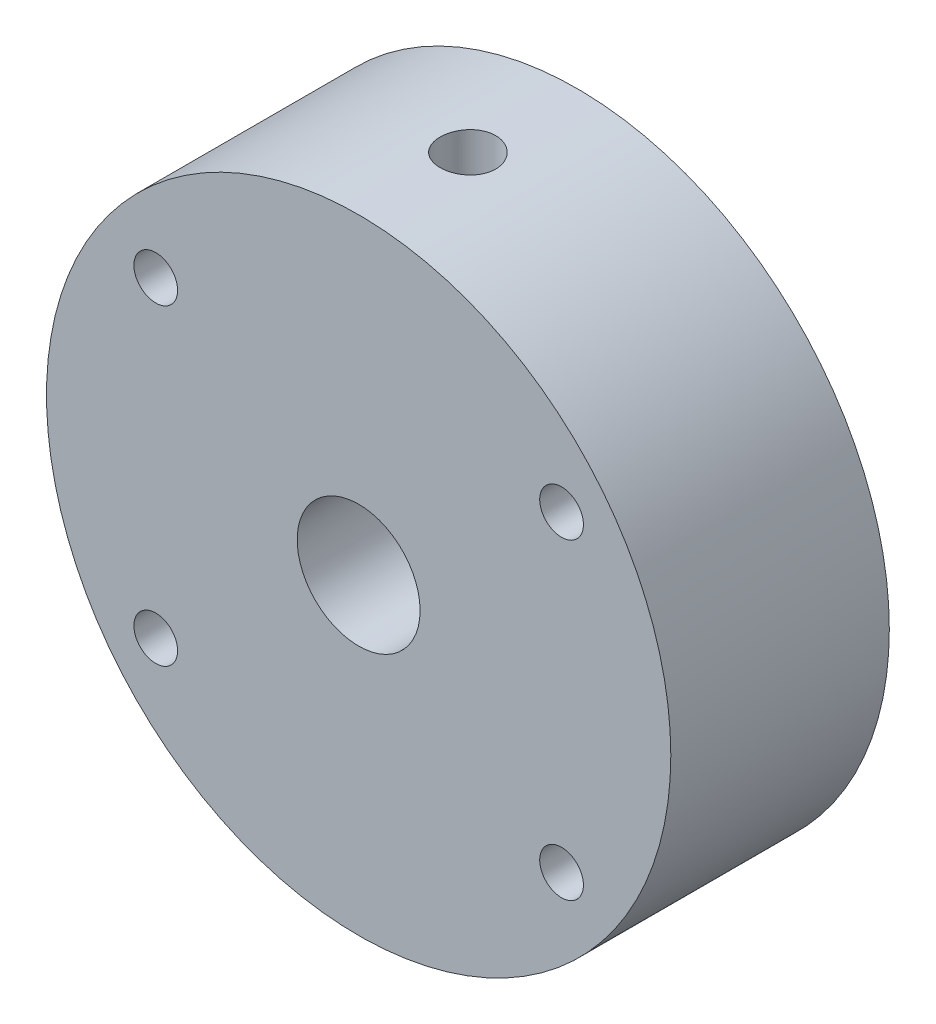
SolidWorks part; units mm, degrees
material "ABS PC"
ref_plane "Front Plane" through (0, 0, 0) normal (0, 0, 1) x (1, 0, 0)
ref_plane "Top Plane" through (0, 0, 0) normal (0, 1, 0) x (1, 0, 0)
ref_plane "Right Plane" through (0, 0, 0) normal (1, 0, 0) x (0, 0, -1)
sketch "Sketch1" plane through (0, 0, 0) normal (0, 0, 1) x (1, 0, 0)
  circle A0 centre (0, 0) radius 12.7
  circle A1 centre (0, 0) radius 2.5
  dimension "D1" = 25.4
  dimension "D2" = 5
extrude "Boss-Extrude1" add sketch "Sketch1" along normal blind 8.89
hole_wizard "#2-56 Tapped Hole1" positions "Sketch4" profile "Sketch3" tap size "#2-56" standard "ANSI Inch" end condition through all
sketch "Sketch4" plane through (0, 0, 8.89) normal (0, 0, 1) x (1, 0, 0)
  line L1 (-8.255, -6.35) -> (8.255, -6.35) construction
  line L2 (-8.255, -6.35) -> (-8.255, 6.35) construction
  line L3 (-8.255, 6.35) -> (8.255, 6.35) construction
  line L4 (8.255, -6.35) -> (8.255, 6.35) construction
  line L5 (-8.255, -6.35) -> (8.255, 6.35) construction
  line L6 (-8.255, 6.35) -> (8.255, -6.35) construction
  circle A0 centre (0, 0) radius 2.5 construction
  point P0 (-8.255, 6.35)
  point P2 (8.255, 6.35)
  point P4 (8.255, -6.35)
  point P6 (-8.255, -6.35)
  dimension "D3" = 5
  dimension "D1" = 12.7
  dimension "D2" = 16.51
sketch "Sketch3" plane through (-8.255, 6.35, 8.89) normal (1, 0, 0) x (0, -1, 0)
  line L0 (0, 0) -> (0, 8.89)
  line L1 (0, 8.89) -> (0.889, 8.89)
  line L2 (0.889, 8.89) -> (0.889, 0)
  line L5 (0.889, 0) -> (0, 0)
  line L11 (0, -6.35) -> (0, 107.95) construction
  dimension "Thru Tap Drill Dia." = 1.778
  dimension "Thru Tap Drill Depth" = 8.89
cosmetic thread "Hole Thread1" parameters "D2"=2.1844
cosmetic thread "Hole Thread2" parameters "D2"=2.1844
cosmetic thread "Hole Thread3" parameters "D2"=2.1844
cosmetic thread "Hole Thread4" parameters "D2"=2.1844
hole_wizard "#4-40 Tapped Hole1" positions "Sketch7" profile "Sketch6" tap size "#4-40" standard "ANSI Inch"
sketch "Sketch7" plane through (0, 0, 0) normal (0, 1, 0) x (1, 0, 0)
  line L0 (-12.7, -8.89) -> (12.7, -8.89) construction
  line L1 (-12.7, -8.89) -> (12.7, -8.89) construction
  line L2 (0, -8.89) -> (0, 0) construction
  point P0 (0, -4.445)
sketch "Sketch6" plane through (0, 0, 4.445) normal (1, 0, 0) x (0, 0, -1)
  line L0 (0, 0) -> (0, 12.7)
  line L1 (0, 12.7) -> (1.1303, 12.7)
  line L2 (1.1303, 12.7) -> (1.1303, 0)
  line L5 (1.1303, 0) -> (0, 0)
  line L11 (0, -6.35) -> (0, 107.95) construction
  dimension "Thru Tap Drill Dia." = 2.2606
  dimension "Thru Tap Drill Depth" = 12.7
cosmetic thread "Hole Thread5" parameters "D2"=2.8448
